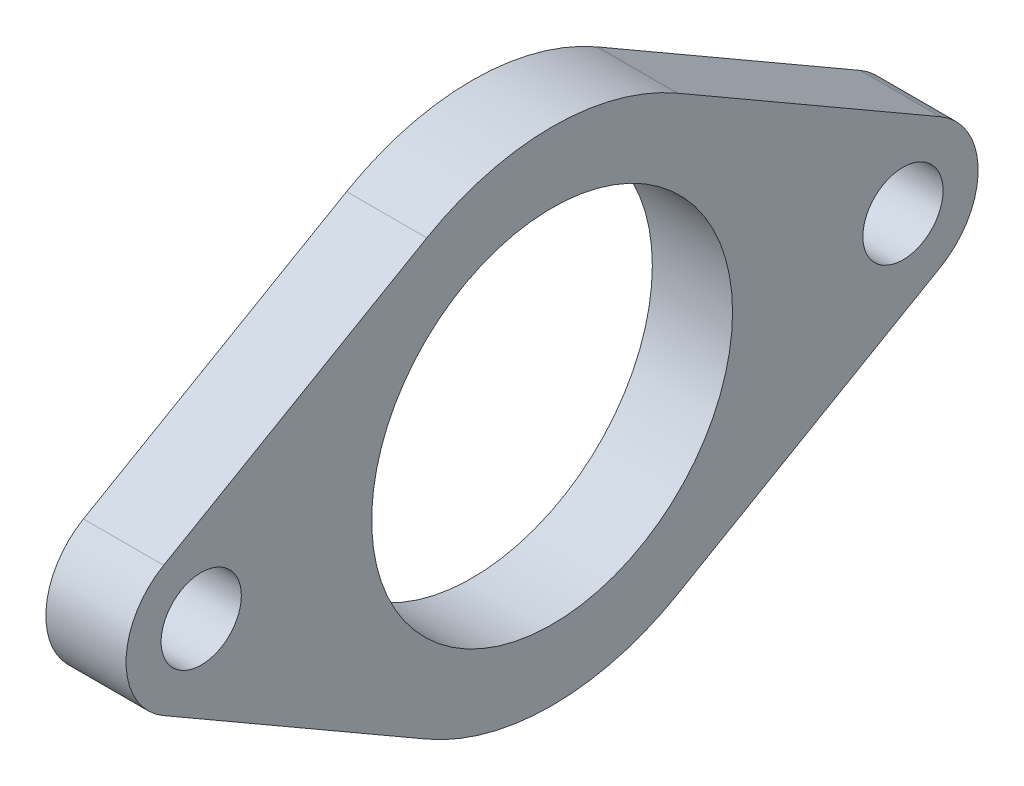
SolidWorks part; units mm, degrees
ref_plane "Front Plane" through (0, 0, 0) normal (0, 0, 1) x (1, 0, 0)
ref_plane "Top Plane" through (0, 0, 0) normal (0, 1, 0) x (1, 0, 0)
ref_plane "Right Plane" through (0, 0, 0) normal (1, 0, 0) x (0, 0, -1)
sketch "Sketch1" plane through (0, 0, 0) normal (1, 0, 0) x (0, 0, -1)
  line L0 (-35, 0) -> (35, 0) construction
  line L1 (-12.5, -21.6506) -> (-38.75, -6.4952)
  line L2 (12.5, -21.6506) -> (38.75, -6.4952)
  line L3 (-38.75, 6.4952) -> (-12.5, 21.6506)
  line L4 (12.5, 21.6506) -> (38.75, 6.4952)
  circle A0 centre (0, 0) radius 18
  circle A1 centre (0, 0) radius 25
  circle A2 centre (-35, 0) radius 7.5
  circle A3 centre (35, 0) radius 7.5
  circle A4 centre (-35, 0) radius 4
  circle A5 centre (35, 0) radius 4
  point P8 (0, 0)
  dimension "D1" = 36
  dimension "D2" = 15
  dimension "D4" = 50
  dimension "D5" = 8
  dimension "D3" = 70
extrude "Boss-Extrude1" add sketch "Sketch1" along normal blind 8
